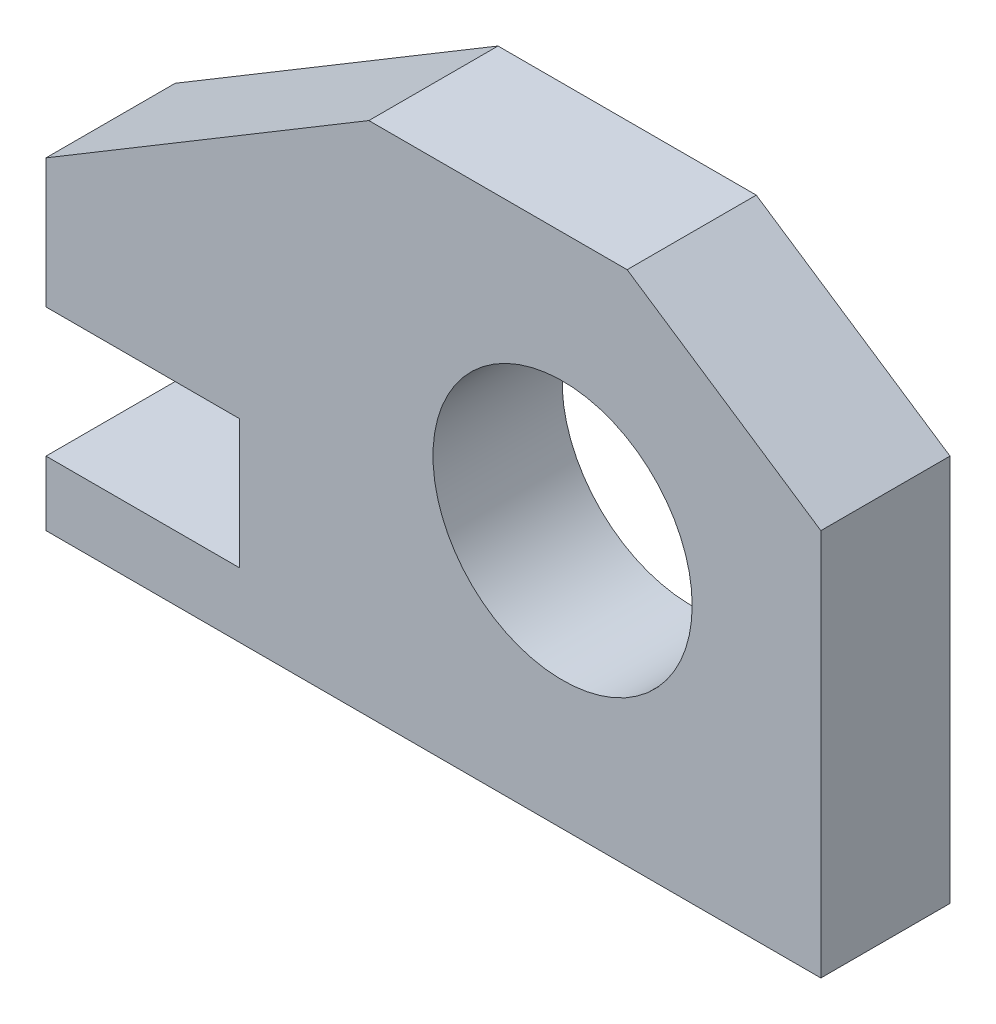
SolidWorks part; units mm, degrees
ref_plane "Front Plane" through (0, 0, 0) normal (0, 0, 1) x (1, 0, 0)
ref_plane "Top Plane" through (0, 0, 0) normal (0, 1, 0) x (1, 0, 0)
ref_plane "Right Plane" through (0, 0, 0) normal (1, 0, 0) x (0, 0, -1)
sketch "Sketch1" plane through (0, 0, 0) normal (0, 0, 1) x (1, 0, 0)
  line L0 (-117.9108, 62.3794) -> (-92.5108, 62.3794)
  line L1 (-92.5108, 62.3794) -> (-73.4608, 49.6794)
  line L2 (-73.4608, 49.6794) -> (-73.4608, 11.5794)
  line L3 (-73.4608, 11.5794) -> (-149.6608, 11.5794)
  line L4 (-149.6608, 11.5794) -> (-149.6608, 17.9294)
  line L5 (-149.6608, 17.9294) -> (-130.6108, 17.9294)
  line L6 (-130.6108, 17.9294) -> (-130.6108, 30.6294)
  line L7 (-130.6108, 30.6294) -> (-149.6608, 30.6294)
  line L8 (-149.6608, 43.3294) -> (-117.9108, 62.3794)
  line L9 (-149.6608, 43.3294) -> (-149.6608, 30.6294)
  dimension "D1" = 25.4
  dimension "D2" = 76.2
  dimension "D3" = 38.1
  dimension "D4" = 50.8
  dimension "D5" = 6.35
  dimension "D6" = 12.7
  dimension "D7" = 19.05
  dimension "D8" = 31.75
  dimension "D9" = 19.05
extrude "Boss-Extrude1" add sketch "Sketch1" along normal blind 12.7 contours L9 L7 L6 L5 L4 L3 L2 L1 L0 L8
sketch "Sketch2" plane through (0, 0, 12.7) normal (0, 0, 1) x (1, 0, 0)
  line L0 (-73.4608, 49.6794) -> (-73.4608, 11.5794) construction
  line L1 (-73.4608, 11.5794) -> (-149.6608, 11.5794) construction
  circle A0 centre (-98.8608, 36.9794) radius 12.7458
  dimension "D1" = 25.4916
  dimension "D2" = 25.4
  dimension "D3" = 25.4
extrude "Cut-Extrude1" cut sketch "Sketch2" against normal through all
